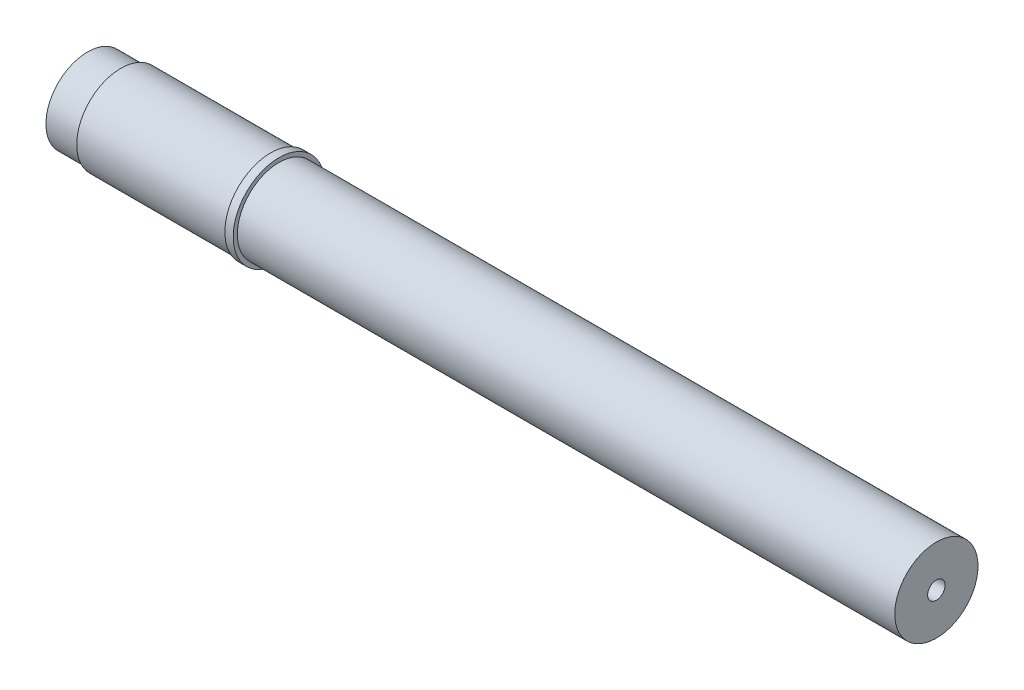
SolidWorks part; units mm, degrees
material "CK45"
ref_plane "Front Plane" through (0, 0, 0) normal (0, 0, 1) x (1, 0, 0)
ref_plane "Top Plane" through (0, 0, 0) normal (0, 1, 0) x (1, 0, 0)
ref_plane "Right Plane" through (0, 0, 0) normal (1, 0, 0) x (0, 0, -1)
sketch "Sketch1" plane through (0, 0, 0) normal (0, 0, 1) x (1, 0, 0)
  line L0 (-32.3439, -25) -> (-12.3439, -25)
  line L1 (-12.3439, -25) -> (-12.3439, -26.5)
  line L2 (-12.3439, -26.5) -> (77.6561, -26.5)
  line L3 (77.6561, -26.5) -> (77.6561, -27.5)
  line L4 (77.6561, -27.5) -> (82.6561, -27.5)
  line L5 (82.6561, -27.5) -> (82.6561, -25)
  line L6 (82.6561, -25) -> (477.6561, -25)
  line L7 (477.6561, -25) -> (477.6561, 0)
  line L8 (477.6561, 0) -> (-32.3439, 0)
  line L9 (-32.3439, 0) -> (-32.3439, -25)
  dimension "D1" = 20
  dimension "D2" = 90
  dimension "D3" = 5
  dimension "D4" = 395
  dimension "D5" = 26.5
  dimension "D6" = 25
  dimension "D7" = 27.5
  dimension "D8" = 25
revolve "Revolve1" add sketch "Sketch1" angle 360 about L8
hole_wizard "Ø10.5 (10.5) Diameter Hole1" positions "3DSketch1" profile "Sketch2" hole size "Ø10.5" standard "ISO"
sketch3d "3DSketch1"
  line L0 (82.6561, 0, 0) -> (477.6561, 0, 0) construction
  point P0 (477.6561, 0, 0)
sketch "Sketch2" plane through (477.6561, 0, 0) normal (0, 1, 0) x (0, 0, -1)
  line L0 (0, 0) -> (0, 38.1545)
  line L1 (0, 38.1545) -> (5.25, 35)
  line L2 (5.25, 35) -> (5.25, 0)
  line L5 (5.25, 0) -> (0, 0)
  line L10 (0, 38.1545) -> (-5.25, 35) construction
  line L11 (0, -6.35) -> (0, 107.95) construction
  dimension "Hole Dia." = 10.5
  dimension "Hole Depth" = 35
  dimension "Drill Angle" = 118
cosmetic thread "Cosmetic Thread1" parameters "D1"=30, "D2"=12
